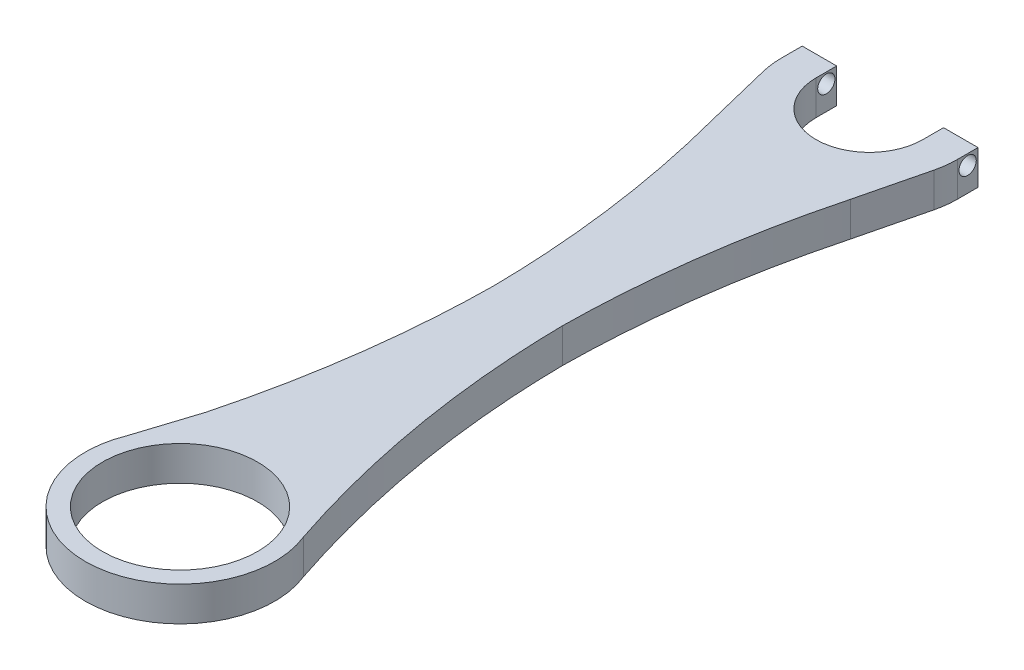
SolidWorks part; units mm, degrees
ref_plane "Front Plane" through (0, 0, 0) normal (0, 0, 1) x (1, 0, 0)
ref_plane "Top Plane" through (0, 0, 0) normal (0, 1, 0) x (1, 0, 0)
ref_plane "Right Plane" through (0, 0, 0) normal (1, 0, 0) x (0, 0, -1)
sketch "Sketch1" plane through (0, 0, 0) normal (0, 1, 0) x (1, 0, 0)
  line L0 (0, 0) -> (0, 26.1848) construction
  line L1 (-25.5, 0) -> (-15.5, 0)
  line L2 (-25.5, 0) -> (-25.5, 6)
  line L3 (-25.5, 6) -> (-15.5, 6)
  line L4 (-15.5, 0) -> (-15.5, 6)
  line L5 (15.5, 0) -> (25.5, 0)
  line L6 (15.5, 0) -> (15.5, 6)
  line L7 (15.5, 6) -> (25.5, 6)
  line L8 (25.5, 0) -> (25.5, 6)
  line L9 (0, -25.5) -> (0, -172.5)
  line L11 (-20, -172.5) -> (-25.5, -189.7044)
  line L13 (20, -172.5) -> (25.5, -189.7044)
  line L14 (0, -99) -> (-10, -99)
  line L15 (0, -99) -> (10, -99)
  line L17 (-20, -25.5) -> (-24.7655, -6.0761)
  line L19 (20, -25.5) -> (24.7655, -6.0761)
  line L21 (-10, -99) -> (10, -99)
  line L22 (-10, -99) -> (-10, -172.5)
  line L23 (-10, -172.5) -> (10, -172.5)
  line L24 (10, -99) -> (10, -172.5)
  line L25 (10, -99) -> (-10, -99)
  arc A0 (-25.5, 0) -> (25.5, 0) centre (0, 0) ccw
  arc A1 (-15.5, 0) -> (15.5, 0) centre (0, 0) ccw
  circle A2 centre (0, -200) radius 22.5
  circle A3 centre (0, -200) radius 27.5
  spline S0 degree 2 poles (-20, -25.5) (-9.5438, -65.2645) (-10, -105.768) knots 0 0 0 1 1 1
  spline S1 degree 2 poles (-20, -172.5) (-9.5438, -132.7355) (-10, -92.232) knots 0 0 0 1 1 1
  spline S2 degree 2 poles (20, -172.5) (9.5438, -132.7355) (10, -92.232) knots 0 0 0 1 1 1
  spline S3 degree 2 poles (20, -25.5) (9.5438, -65.2645) (10, -105.768) knots 0 0 0 1 1 1
  point P19 (0, 0)
  point P46 (0, 0)
  point P47 (0, 0)
  dimension "D6" = 45
  dimension "D7" = 55
  dimension "D1" = 6
  dimension "D2" = 10
  dimension "D3" = 10
  dimension "D4" = 15.5
  dimension "D5" = 15.5
  dimension "D8" = 200
  dimension "D9" = 20
  dimension "D10" = 20
  dimension "D11" = 10
  dimension "D12" = 10
  dimension "D13" = 20
  dimension "D14" = 20
extrude "Boss-Extrude1" add sketch "Sketch1" along normal blind 10
sketch "Sketch3" plane through (0, 10, 0) normal (0, 1, 0) x (1, 0, 0)
  line L0 (10, -174.3826) -> (25.5, -189.7044)
  line L1 (-10, -99) -> (10, -99)
  line L2 (-10, -99) -> (-10, -174.3826)
  line L3 (-10, -174.3826) -> (10, -174.3826)
  line L4 (10, -99) -> (10, -174.3826)
  circle A0 centre (0, -200) radius 27.5 construction
  spline S0 degree 2 poles (25.5, -189.7044) (9.43, -141.674) (10, -92.232) knots 0 0 0 1 1 1
  arc M3 (-25.5, -189.7044) -> (0, -172.5) centre (0, -200) ccw
  line M4 (0, -172.5) -> (-10, -172.5)
  line M5 (-10, -172.5) -> (-10, -99)
extrude "Boss-Extrude6" add sketch "Sketch3" against normal blind 10 contours L4 L1 M5 M4 M3 | S0 L4 M3
sketch "Sketch4" plane through (-25.5, 0, 0) normal (-1, 0, 0) x (0, 0, 1)
  line L0 (0, 10) -> (-6, 10) construction
  line L1 (-6, 10) -> (-6, 0) construction
  circle A0 centre (-3, 7) radius 2.5
  dimension "D1" = 5
  dimension "D2" = 3
  dimension "D3" = 3
extrude "Cut-Extrude1" cut sketch "Sketch4" against normal through all
